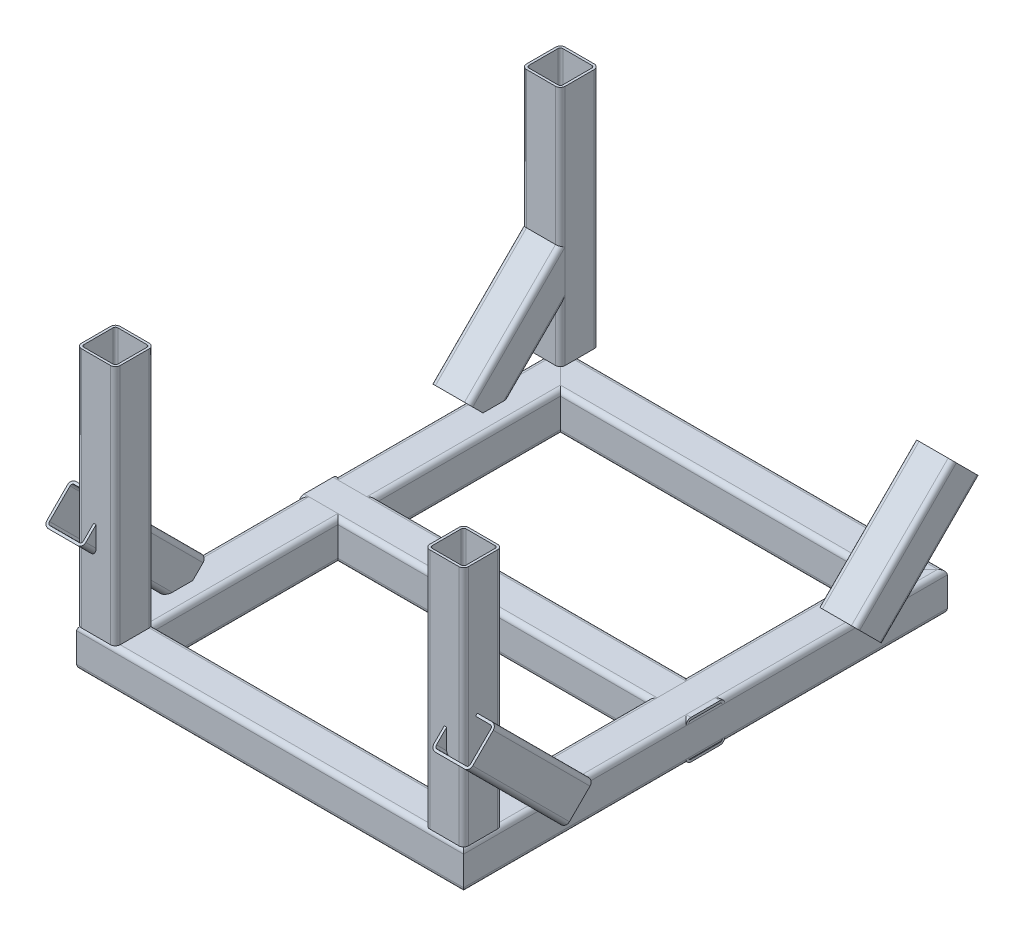
SolidWorks part; units mm, degrees
ref_plane "Front Plane" through (0, 0, 0) normal (0, 0, 1) x (1, 0, 0)
ref_plane "Top Plane" through (0, 0, 0) normal (0, 1, 0) x (1, 0, 0)
ref_plane "Right Plane" through (0, 0, 0) normal (1, 0, 0) x (0, 0, -1)
sketch "Sketch3" plane through (0, 0, 0) normal (0, 1, 0) x (1, 0, 0)
  line L1 (-400, 500) -> (400, 500)
  line L2 (-400, 500) -> (-400, -500)
  line L3 (-400, -500) -> (400, -500)
  line L4 (400, 500) -> (400, -500)
  line L5 (-400, 500) -> (400, -500) construction
  line L6 (-400, -500) -> (400, 500) construction
  line L7 (-400, 0) -> (400, 0)
  point P0 (0, 0)
  dimension "D1" = 1000
  dimension "D2" = 800
sketch3d "3DSketch7"
  line L0 (-400, 0, -500) -> (-400, 500, -500)
  line L1 (400, 0, 500) -> (400, 500, 500)
  line L2 (-400, 200, 500) -> (-400, 0, 300)
  line L3 (-400, 0, -500) -> (-400, 0, 500) construction
  line L4 (-5002.1602, -1212.8616, 400) -> (-4984.7604, -1207.4539, 400)
  line L5 (400, 0, -500) -> (400, 500, -500)
  line L6 (400, 200, 500) -> (400, 0, 300)
  line L7 (400, 200, -500) -> (400, 0, -300)
  line L8 (-400, 0, 500) -> (-400, 500, 500)
  line L9 (-400, 200, -500) -> (-400, 0, -300)
  dimension "D2" = 200
  dimension "D1" = 500
  dimension "D3" = 200
other "Square tube 80 X 80 X 5(1)"
ref_plane "Plane1" through (360, -40, -500) normal (0, 0, 1) x (1, 0, 0)
sketch "Sketch11" plane through (360, -40, -500) normal (0, 0, 1) x (1, 0, 0)
  line L0 (-30, -35) -> (30, -35)
  line L1 (-35, -30) -> (-35, 30)
  line L2 (30, 35) -> (-30, 35)
  line L3 (35, 30) -> (35, -30)
  line L4 (-30, -40) -> (30, -40)
  line L5 (-40, -30) -> (-40, 30)
  line L6 (30, 40) -> (-30, 40)
  line L7 (40, 30) -> (40, -30)
  arc A0 (40, 30) -> (30, 40) centre (30, 30) ccw
  arc A1 (30, -40) -> (40, -30) centre (30, -30) ccw
  arc A2 (-40, -30) -> (-30, -40) centre (-30, -30) ccw
  arc A3 (-30, 40) -> (-40, 30) centre (-30, 30) ccw
  arc A4 (-30, 35) -> (-35, 30) centre (-30, 30) ccw
  arc A5 (35, 30) -> (30, 35) centre (30, 30) ccw
  arc A6 (30, -35) -> (35, -30) centre (30, -30) ccw
  arc A7 (-35, -30) -> (-30, -35) centre (-30, -30) ccw
  point P0 (-40, 0)
  point P1 (40, 0)
  point P2 (0, 40)
  point P3 (0, -40)
  point P4 (0, 0)
  point P5 (-40, -40)
  point P6 (40, -40)
  point P7 (40, 40)
  point P8 (-40, 40)
  point P33 (0, 0)
  dimension "D1" = 10
  dimension "Thickness" = 5
  dimension "V_leg" = 80
other "Square tube 80 X 80 X 5(2)"
ref_plane "Plane2" through (-400, -40, 0) normal (1, 0, 0) x (0, 0, -1)
sketch "Sketch1" plane through (-400, -40, 0) normal (1, 0, 0) x (0, 0, -1)
  line L0 (-30, -35) -> (30, -35)
  line L1 (-35, -30) -> (-35, 30)
  line L2 (30, 35) -> (-30, 35)
  line L3 (35, 30) -> (35, -30)
  line L4 (-30, -40) -> (30, -40)
  line L5 (-40, -30) -> (-40, 30)
  line L6 (30, 40) -> (-30, 40)
  line L7 (40, 30) -> (40, -30)
  arc A0 (40, 30) -> (30, 40) centre (30, 30) ccw
  arc A1 (30, -40) -> (40, -30) centre (30, -30) ccw
  arc A2 (-40, -30) -> (-30, -40) centre (-30, -30) ccw
  arc A3 (-30, 40) -> (-40, 30) centre (-30, 30) ccw
  arc A4 (-30, 35) -> (-35, 30) centre (-30, 30) ccw
  arc A5 (35, 30) -> (30, 35) centre (30, 30) ccw
  arc A6 (30, -35) -> (35, -30) centre (30, -30) ccw
  arc A7 (-35, -30) -> (-30, -35) centre (-30, -30) ccw
  point P0 (-40, 0)
  point P1 (40, 0)
  point P2 (0, 40)
  point P3 (0, -40)
  point P4 (0, 0)
  point P5 (-40, -40)
  point P6 (40, -40)
  point P7 (40, 40)
  point P8 (-40, 40)
  point P33 (0, 0)
  dimension "D1" = 10
  dimension "Thickness" = 5
  dimension "V_leg" = 80
other "Square tube 80 X 80 X 5(3)"
ref_plane "Plane3" through (-360, 0, 460) normal (0, 1, 0) x (1, 0, 0)
sketch "Sketch12" plane through (-360, 0, 460) normal (0, 1, 0) x (1, 0, 0)
  line L0 (-30, -35) -> (30, -35)
  line L1 (-35, -30) -> (-35, 30)
  line L2 (30, 35) -> (-30, 35)
  line L3 (35, 30) -> (35, -30)
  line L4 (-30, -40) -> (30, -40)
  line L5 (-40, -30) -> (-40, 30)
  line L6 (30, 40) -> (-30, 40)
  line L7 (40, 30) -> (40, -30)
  arc A0 (40, 30) -> (30, 40) centre (30, 30) ccw
  arc A1 (30, -40) -> (40, -30) centre (30, -30) ccw
  arc A2 (-40, -30) -> (-30, -40) centre (-30, -30) ccw
  arc A3 (-30, 40) -> (-40, 30) centre (-30, 30) ccw
  arc A4 (-30, 35) -> (-35, 30) centre (-30, 30) ccw
  arc A5 (35, 30) -> (30, 35) centre (30, 30) ccw
  arc A6 (30, -35) -> (35, -30) centre (30, -30) ccw
  arc A7 (-35, -30) -> (-30, -35) centre (-30, -30) ccw
  point P0 (-40, 0)
  point P1 (40, 0)
  point P2 (0, 40)
  point P3 (0, -40)
  point P4 (0, 0)
  point P5 (-40, -40)
  point P6 (40, -40)
  point P7 (40, 40)
  point P8 (-40, 40)
  point P33 (0, 0)
  dimension "D1" = 10
  dimension "Thickness" = 5
  dimension "V_leg" = 80
other "Square tube 80 X 80 X 5(8)"
ref_plane "Plane5" through (-400, 200, -500) normal (0, -0.7071, 0.7071) x (1, 0, 0)
sketch "Sketch14" plane through (-400, 200, -500) normal (0, -0.7071, 0.7071) x (1, 0, 0)
  line L0 (-30, -35) -> (30, -35)
  line L1 (-35, -30) -> (-35, 30)
  line L2 (30, 35) -> (-30, 35)
  line L3 (35, 30) -> (35, -30)
  line L4 (-30, -40) -> (30, -40)
  line L5 (-40, -30) -> (-40, 30)
  line L6 (30, 40) -> (-30, 40)
  line L7 (40, 30) -> (40, -30)
  arc A0 (40, 30) -> (30, 40) centre (30, 30) ccw
  arc A1 (30, -40) -> (40, -30) centre (30, -30) ccw
  arc A2 (-40, -30) -> (-30, -40) centre (-30, -30) ccw
  arc A3 (-30, 40) -> (-40, 30) centre (-30, 30) ccw
  arc A4 (-30, 35) -> (-35, 30) centre (-30, 30) ccw
  arc A5 (35, 30) -> (30, 35) centre (30, 30) ccw
  arc A6 (30, -35) -> (35, -30) centre (30, -30) ccw
  arc A7 (-35, -30) -> (-30, -35) centre (-30, -30) ccw
  point P0 (-40, 0)
  point P1 (40, 0)
  point P2 (0, 40)
  point P3 (0, -40)
  point P4 (0, 0)
  point P5 (-40, -40)
  point P6 (40, -40)
  point P7 (40, 40)
  point P8 (-40, 40)
  point P33 (0, 0)
  dimension "D1" = 10
  dimension "Thickness" = 5
  dimension "V_leg" = 80
other "Square tube 80 X 80 X 5(11)"
ref_plane "Plane8" through (360, 0, 460) normal (0, 1, 0) x (1, 0, 0)
sketch "Sketch17" plane through (360, 0, 460) normal (0, 1, 0) x (1, 0, 0)
  line L0 (-30, -35) -> (30, -35)
  line L1 (-35, -30) -> (-35, 30)
  line L2 (30, 35) -> (-30, 35)
  line L3 (35, 30) -> (35, -30)
  line L4 (-30, -40) -> (30, -40)
  line L5 (-40, -30) -> (-40, 30)
  line L6 (30, 40) -> (-30, 40)
  line L7 (40, 30) -> (40, -30)
  arc A0 (40, 30) -> (30, 40) centre (30, 30) ccw
  arc A1 (30, -40) -> (40, -30) centre (30, -30) ccw
  arc A2 (-40, -30) -> (-30, -40) centre (-30, -30) ccw
  arc A3 (-30, 40) -> (-40, 30) centre (-30, 30) ccw
  arc A4 (-30, 35) -> (-35, 30) centre (-30, 30) ccw
  arc A5 (35, 30) -> (30, 35) centre (30, 30) ccw
  arc A6 (30, -35) -> (35, -30) centre (30, -30) ccw
  arc A7 (-35, -30) -> (-30, -35) centre (-30, -30) ccw
  point P0 (-40, 0)
  point P1 (40, 0)
  point P2 (0, 40)
  point P3 (0, -40)
  point P4 (0, 0)
  point P5 (-40, -40)
  point P6 (40, -40)
  point P7 (40, 40)
  point P8 (-40, 40)
  point P33 (0, 0)
  dimension "D1" = 10
  dimension "Thickness" = 5
  dimension "V_leg" = 80
other "Square tube 80 X 80 X 5(12)"
ref_plane "Plane9" through (-400, 0, -500) normal (0, 1, 0) x (1, 0, 0)
sketch "Sketch18" plane through (-400, 0, -500) normal (0, 1, 0) x (1, 0, 0)
  line L0 (-30, -35) -> (30, -35)
  line L1 (-35, -30) -> (-35, 30)
  line L2 (30, 35) -> (-30, 35)
  line L3 (35, 30) -> (35, -30)
  line L4 (-30, -40) -> (30, -40)
  line L5 (-40, -30) -> (-40, 30)
  line L6 (30, 40) -> (-30, 40)
  line L7 (40, 30) -> (40, -30)
  arc A0 (40, 30) -> (30, 40) centre (30, 30) ccw
  arc A1 (30, -40) -> (40, -30) centre (30, -30) ccw
  arc A2 (-40, -30) -> (-30, -40) centre (-30, -30) ccw
  arc A3 (-30, 40) -> (-40, 30) centre (-30, 30) ccw
  arc A4 (-30, 35) -> (-35, 30) centre (-30, 30) ccw
  arc A5 (35, 30) -> (30, 35) centre (30, 30) ccw
  arc A6 (30, -35) -> (35, -30) centre (30, -30) ccw
  arc A7 (-35, -30) -> (-30, -35) centre (-30, -30) ccw
  point P0 (-40, 0)
  point P1 (40, 0)
  point P2 (0, 40)
  point P3 (0, -40)
  point P4 (0, 0)
  point P5 (-40, -40)
  point P6 (40, -40)
  point P7 (40, 40)
  point P8 (-40, 40)
  point P33 (0, 0)
  dimension "D1" = 10
  dimension "Thickness" = 5
  dimension "V_leg" = 80
